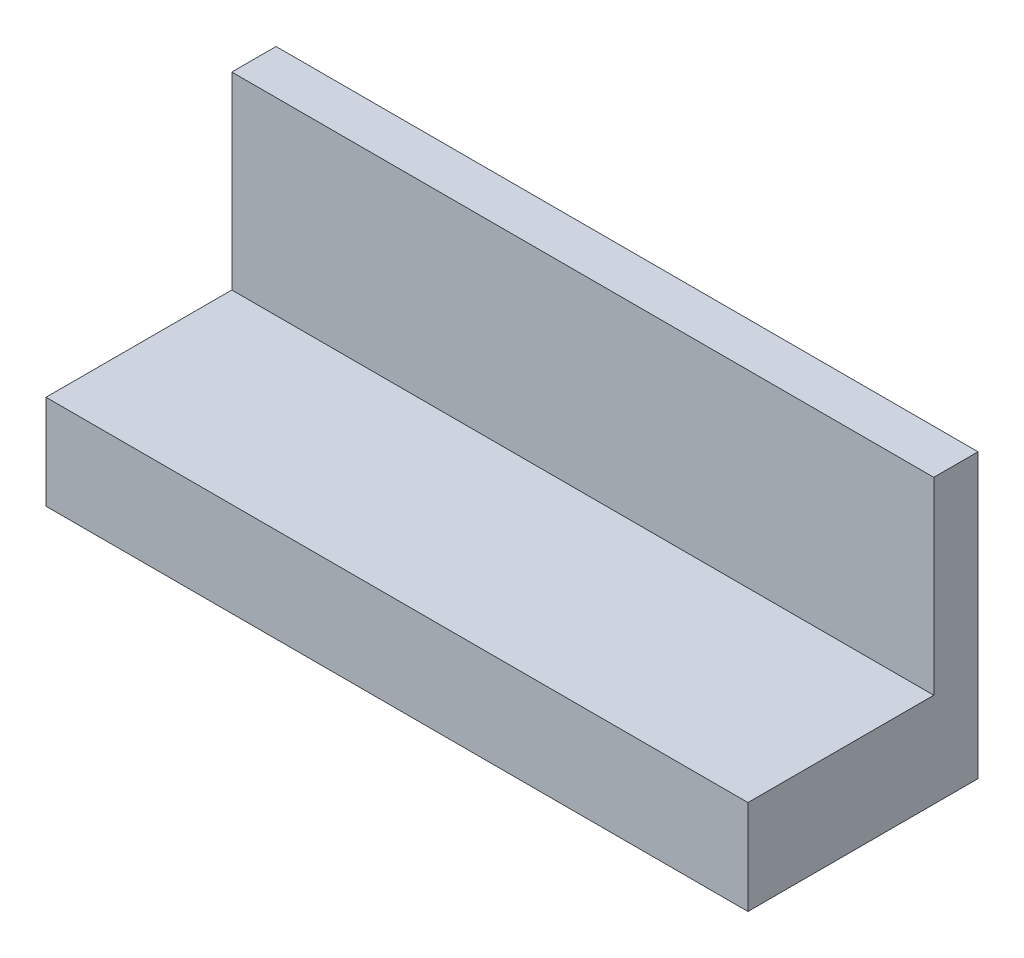
SolidWorks part; units mm, degrees
material "ABS"
ref_plane "Front Plane" through (0, 0, 0) normal (0, 0, 1) x (1, 0, 0)
ref_plane "Top Plane" through (0, 0, 0) normal (0, 1, 0) x (1, 0, 0)
ref_plane "Right Plane" through (0, 0, 0) normal (1, 0, 0) x (0, 0, -1)
sketch "Sketch1" plane through (0, 0, 0) normal (0, 0, 1) x (1, 0, 0)
  line L1 (0, 0) -> (23.8, 0)
  line L2 (0, 0) -> (0, 3.2)
  line L3 (0, 3.2) -> (23.8, 3.2)
  line L4 (23.8, 0) -> (23.8, 3.2)
  dimension "D1" = 3.2
  dimension "D2" = 23.8
extrude "Boss-Extrude1" add sketch "Sketch1" against normal blind 7.8
shell "Shell1" thickness 1.2
sketch "Sketch3" plane through (0, 2, 0) normal (0, -1, 0) x (1, 0, 0)
  line L0 (0, 0) -> (23.8, 0) construction
  line L1 (23.8, -7.8) -> (23.8, 0) construction
  circle A0 centre (15.9, -3.9) radius 1.5
  circle A1 centre (15.9, -3.9) radius 0.6
  dimension "D1" = 3
  dimension "D2" = 1.2
  dimension "D3" = 3.9
  dimension "D4" = 7.9
extrude "Boss-Extrude3" add sketch "Sketch3" along normal offset from surface (1.8 mm away) 0.2 up to face at (11.9, 0, -3.9)
pattern_linear "LPattern1" count 2 spacing 8 along (-1, 0, 0) of "Boss-Extrude3"
ref_plane "Plane1" through (0, 0, -7.8) normal (0, 0, -1) x (-1, 0, 0)
sketch "Sketch4" plane through (0, 0, -7.8) normal (0, 0, -1) x (-1, 0, 0)
  line L0 (-23.8, 3.2) -> (-23.8, 9.6)
  line L1 (0, 3.2) -> (0, 9.6)
  line L2 (0, 9.6) -> (-23.8, 9.6)
  line L7 (0, 0) -> (0, 3.2)
  line L8 (0, 3.2) -> (-23.8, 3.2)
  line L9 (-23.8, 3.2) -> (-23.8, 0)
  line L10 (-23.8, 0) -> (0, 0)
  line L11 (0, 0) -> (0, 3.2)
  line L13 (-23.8, 3.2) -> (-23.8, 0)
  line L14 (-23.8, 0) -> (0, 0)
  dimension "D1" = 6.4
  dimension "D2" = 0
extrude "Boss-Extrude4" add sketch "Sketch4" against normal blind 1.5
